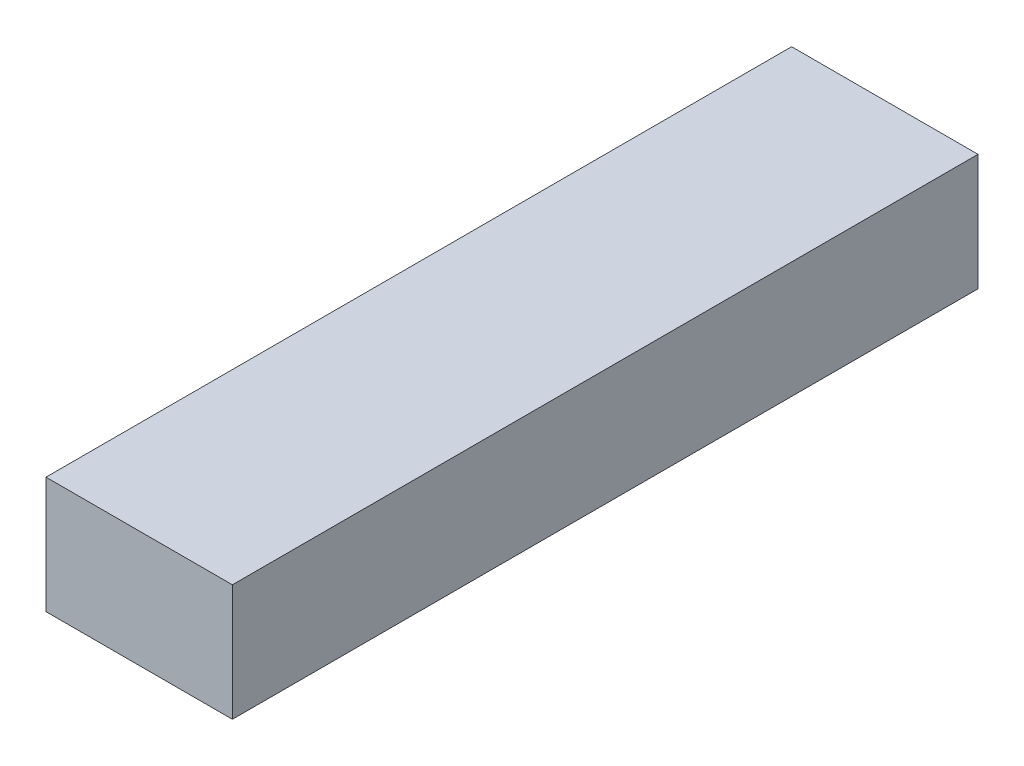
SolidWorks part; units mm, degrees
ref_plane "Front Plane" through (0, 0, 0) normal (0, 0, 1) x (1, 0, 0)
ref_plane "Top Plane" through (0, 0, 0) normal (0, 1, 0) x (1, 0, 0)
ref_plane "Right Plane" through (0, 0, 0) normal (1, 0, 0) x (0, 0, -1)
sketch "Sketch1" plane through (0, 0, 0) normal (0, 1, 0) x (1, 0, 0)
  line L1 (-5.08, 20.32) -> (5.08, 20.32)
  line L2 (-5.08, 20.32) -> (-5.08, -20.32)
  line L3 (-5.08, -20.32) -> (5.08, -20.32)
  line L4 (5.08, 20.32) -> (5.08, -20.32)
  point P7 (0, -31.75)
  point P9 (0.0747, 9.5624)
  dimension "D1" = 10.16
  dimension "D2" = 40.64
  dimension "D3" = 5.08
  dimension "D4" = 20.32
extrude "Boss-Extrude1" add sketch "Sketch1" along normal blind 6.35
